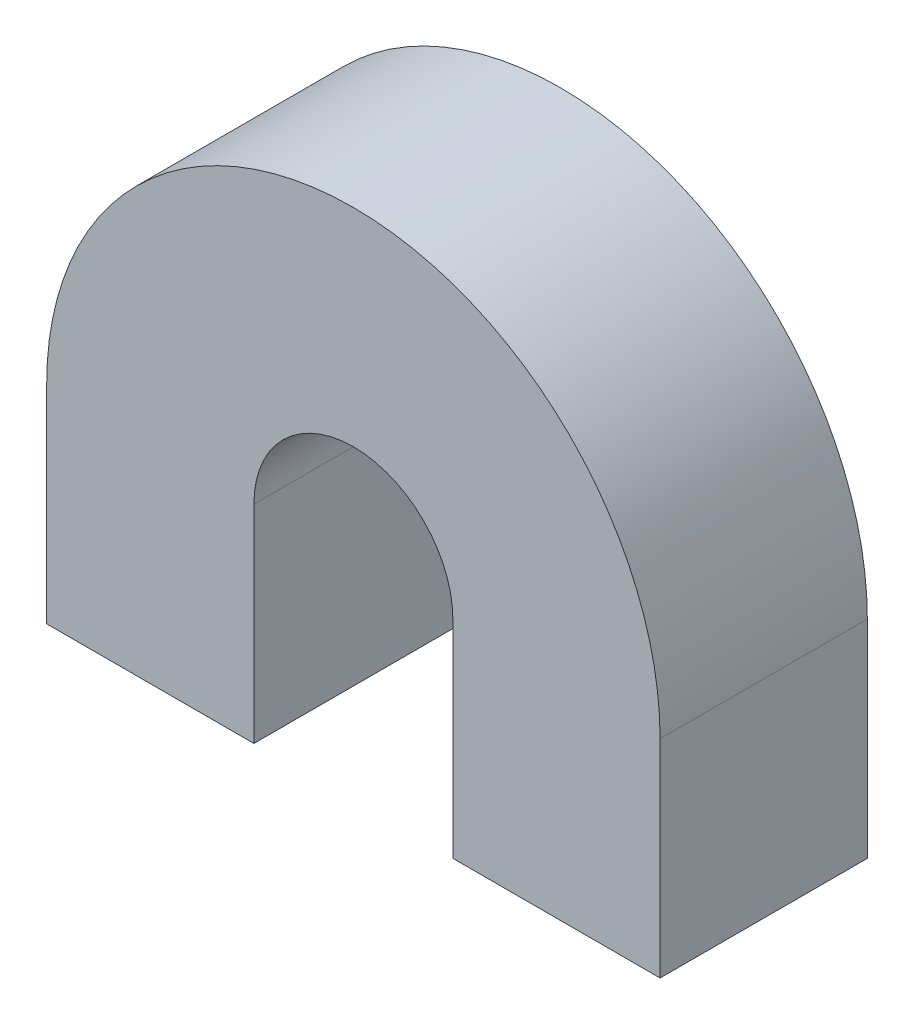
SolidWorks part; units mm, degrees
ref_plane "Ebene vorne" through (0, 0, 0) normal (0, 0, 1) x (1, 0, 0)
ref_plane "Ebene oben" through (0, 0, 0) normal (0, 1, 0) x (1, 0, 0)
ref_plane "Ebene rechts" through (0, 0, 0) normal (1, 0, 0) x (0, 0, -1)
sketch "Sketch1" plane through (0, 0, 0) normal (0, 0, 1) x (1, 0, 0)
  line L0 (-4.8, 8.1867) -> (-4.8, 18.1867)
  line L1 (4.8, 18.1867) -> (4.8, 8.1867)
  line L2 (-4.8, 8.1867) -> (-14.8, 8.1867)
  line L3 (-14.8, 8.1867) -> (-14.8, 18.1867)
  line L4 (0, 0) -> (0, 24.8533) construction
  line L5 (14.8, 8.1867) -> (14.8, 18.1867)
  line L6 (14.8, 8.1867) -> (4.8, 8.1867)
  arc A0 (-4.8, 18.1867) -> (4.8, 18.1867) centre (0, 18.1867) cw
  arc A1 (-14.8, 18.1867) -> (14.8, 18.1867) centre (0, 18.1867) cw
  dimension "D1" = 9.6
  dimension "D2" = 10
  dimension "D3" = 10
extrude "Boss-Extrude1" add sketch "Sketch1" along normal blind 10
